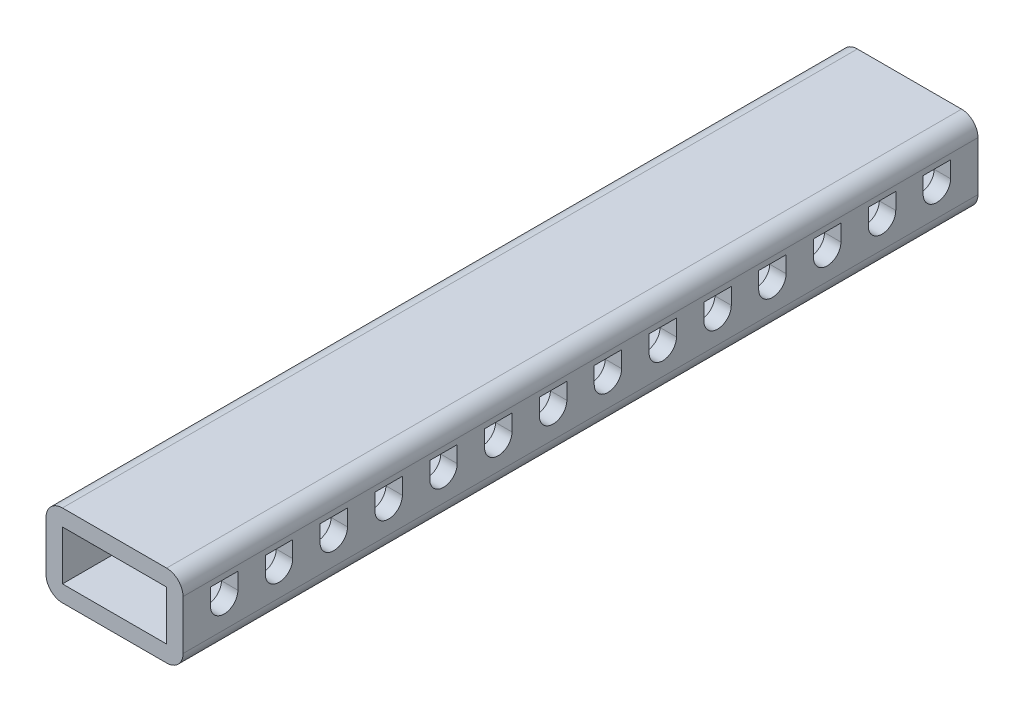
SolidWorks part; units mm, degrees
ref_plane "Front Plane" through (0, 0, 0) normal (0, 0, 1) x (1, 0, 0)
ref_plane "Top Plane" through (0, 0, 0) normal (0, 1, 0) x (1, 0, 0)
ref_plane "Right Plane" through (0, 0, 0) normal (1, 0, 0) x (0, 0, -1)
sketch "Sketch1" plane through (0, 0, 0) normal (0, 0, 1) x (1, 0, 0)
  line L1 (-12.5, 7.5) -> (12.5, 7.5)
  line L2 (-12.5, 7.5) -> (-12.5, -7.5)
  line L3 (-12.5, -7.5) -> (12.5, -7.5)
  line L4 (12.5, 7.5) -> (12.5, -7.5)
  line L5 (-12.5, 7.5) -> (12.5, -7.5) construction
  line L6 (-12.5, -7.5) -> (12.5, 7.5) construction
  point P0 (0, 0)
  dimension "D1" = 25
  dimension "D2" = 15
extrude "Boss-Extrude1" add sketch "Sketch1" along normal blind 145
sketch "Sketch2" plane through (0, 0, 145) normal (0, 0, 1) x (1, 0, 0)
  line L0 (-12.5, 7.5) -> (-12.5, -7.5) construction
  line L1 (-9.5, -4.5) -> (9.5, -4.5)
  line L2 (-9.5, -4.5) -> (-9.5, 4.5)
  line L3 (-9.5, 4.5) -> (9.5, 4.5)
  line L4 (9.5, -4.5) -> (9.5, 4.5)
  line L5 (-9.5, -4.5) -> (9.5, 4.5) construction
  line L6 (-9.5, 4.5) -> (9.5, -4.5) construction
  line L7 (12.5, 7.5) -> (-12.5, 7.5) construction
  point P0 (0, 0)
  dimension "D1" = 3
  dimension "D2" = 3
extrude "Cut-Extrude1" cut sketch "Sketch2" against normal blind 263
sketch "Sketch3" plane through (12.5, 0, 0) normal (1, 0, 0) x (0, 0, -1)
  line L1 (-145, 7.5) -> (0, 7.5) construction
  line L2 (-140, 3.5) -> (-135, 3.5)
  line L3 (-140, 3.5) -> (-140, 0.5)
  line L5 (-135, 3.5) -> (-135, 0.5)
  line L6 (-145, -7.5) -> (-145, 7.5) construction
  line L7 (-132.5, 7.5) -> (-132.5, 3.8883) construction
  line L8 (-130, 3.5) -> (-130, 0.5)
  line L9 (-125, 3.5) -> (-125, 0.5)
  line L10 (-125, 3.5) -> (-130, 3.5)
  line L11 (-122.5, 7.5) -> (-122.5, 3.8883) construction
  line L12 (-112.5, 7.5) -> (-112.5, 3.8883) construction
  line L13 (-120, 3.5) -> (-115, 3.5)
  line L14 (-120, 3.5) -> (-120, 0.5)
  line L15 (-115, 3.5) -> (-115, 0.5)
  line L16 (-110, 3.5) -> (-110, 0.5)
  line L17 (-105, 3.5) -> (-105, 0.5)
  line L18 (-105, 3.5) -> (-110, 3.5)
  line L19 (-102.5, 7.5) -> (-102.5, 3.8883) construction
  line L20 (-92.5, 7.5) -> (-92.5, 3.8883) construction
  line L21 (-110, 3.5) -> (-110, 0.5)
  line L22 (-105, 3.5) -> (-105, 0.5)
  line L23 (-105, 3.5) -> (-110, 3.5)
  line L24 (-100, 3.5) -> (-95, 3.5)
  line L25 (-100, 3.5) -> (-100, 0.5)
  line L26 (-95, 3.5) -> (-95, 0.5)
  line L27 (-90, 3.5) -> (-90, 0.5)
  line L28 (-85, 3.5) -> (-85, 0.5)
  line L29 (-85, 3.5) -> (-90, 3.5)
  line L30 (-82.5, 7.5) -> (-82.5, 3.8883) construction
  line L31 (-72.5, 7.5) -> (-72.5, 3.8883) construction
  line L32 (-62.5, 7.5) -> (-62.5, 3.8883) construction
  line L33 (-52.5, 7.5) -> (-52.5, 3.8883) construction
  line L34 (-90, 3.5) -> (-90, 0.5)
  line L35 (-85, 3.5) -> (-85, 0.5)
  line L36 (-85, 3.5) -> (-90, 3.5)
  line L37 (-80, 3.5) -> (-75, 3.5)
  line L38 (-80, 3.5) -> (-80, 0.5)
  line L39 (-75, 3.5) -> (-75, 0.5)
  line L40 (-80, 3.5) -> (-75, 3.5)
  line L41 (-80, 3.5) -> (-80, 0.5)
  line L42 (-75, 3.5) -> (-75, 0.5)
  line L43 (-70, 3.5) -> (-70, 0.5)
  line L44 (-65, 3.5) -> (-65, 0.5)
  line L45 (-65, 3.5) -> (-70, 3.5)
  line L46 (-60, 3.5) -> (-55, 3.5)
  line L47 (-60, 3.5) -> (-60, 0.5)
  line L48 (-55, 3.5) -> (-55, 0.5)
  line L49 (-50, 3.5) -> (-50, 0.5)
  line L50 (-45, 3.5) -> (-45, 0.5)
  line L51 (-45, 3.5) -> (-50, 3.5)
  line L52 (-42.5, 7.5) -> (-42.5, 3.8883) construction
  line L53 (-32.5, 7.5) -> (-32.5, 3.8883) construction
  line L54 (-22.5, 7.5) -> (-22.5, 3.8883) construction
  line L55 (-12.5, 7.5) -> (-12.5, 3.8883) construction
  line L56 (-2.5, 7.5) -> (-2.5, 3.8883) construction
  line L57 (7.5, 7.5) -> (7.5, 3.8883) construction
  line L58 (17.5, 7.5) -> (17.5, 3.8883) construction
  line L59 (27.5, 7.5) -> (27.5, 3.8883) construction
  line L60 (-50, 3.5) -> (-50, 0.5)
  line L61 (-45, 3.5) -> (-45, 0.5)
  line L62 (-45, 3.5) -> (-50, 3.5)
  line L63 (-40, 3.5) -> (-35, 3.5)
  line L64 (-40, 3.5) -> (-40, 0.5)
  line L65 (-35, 3.5) -> (-35, 0.5)
  line L66 (-30, 3.5) -> (-30, 0.5)
  line L67 (-25, 3.5) -> (-25, 0.5)
  line L68 (-25, 3.5) -> (-30, 3.5)
  line L69 (-30, 3.5) -> (-30, 0.5)
  line L70 (-25, 3.5) -> (-25, 0.5)
  line L71 (-25, 3.5) -> (-30, 3.5)
  line L72 (-20, 3.5) -> (-15, 3.5)
  line L73 (-20, 3.5) -> (-20, 0.5)
  line L74 (-15, 3.5) -> (-15, 0.5)
  line L75 (-20, 3.5) -> (-15, 3.5)
  line L76 (-20, 3.5) -> (-20, 0.5)
  line L77 (-15, 3.5) -> (-15, 0.5)
  line L78 (-10, 3.5) -> (-10, 0.5)
  line L79 (-5, 3.5) -> (-5, 0.5)
  line L80 (-5, 3.5) -> (-10, 3.5)
  line L81 (0, 3.5) -> (5, 3.5)
  line L82 (0, 3.5) -> (0, 0.5)
  line L83 (5, 3.5) -> (5, 0.5)
  line L84 (0, 3.5) -> (5, 3.5)
  line L85 (0, 3.5) -> (0, 0.5)
  line L86 (5, 3.5) -> (5, 0.5)
  line L87 (10, 3.5) -> (10, 0.5)
  line L88 (15, 3.5) -> (15, 0.5)
  line L89 (15, 3.5) -> (10, 3.5)
  line L90 (20, 3.5) -> (25, 3.5)
  line L91 (20, 3.5) -> (20, 0.5)
  line L92 (25, 3.5) -> (25, 0.5)
  line L93 (30, 3.5) -> (30, 0.5)
  line L94 (35, 3.5) -> (35, 0.5)
  line L95 (35, 3.5) -> (30, 3.5)
  line L96 (30, 3.5) -> (30, 0.5)
  line L97 (60, 3.5) -> (65, 3.5)
  line L98 (60, 3.5) -> (60, 0.5)
  line L99 (65, 3.5) -> (65, 0.5)
  line L100 (37.5, 7.5) -> (37.5, 3.8883) construction
  line L101 (47.5, 7.5) -> (47.5, 3.8883) construction
  line L102 (57.5, 7.5) -> (57.5, 3.8883) construction
  line L103 (35, 3.5) -> (35, 0.5)
  line L104 (35, 3.5) -> (30, 3.5)
  line L105 (40, 3.5) -> (45, 3.5)
  line L106 (40, 3.5) -> (40, 0.5)
  line L107 (45, 3.5) -> (45, 0.5)
  line L108 (50, 3.5) -> (50, 0.5)
  line L109 (55, 3.5) -> (55, 0.5)
  line L110 (55, 3.5) -> (50, 3.5)
  line L111 (50, 3.5) -> (50, 0.5)
  line L112 (55, 3.5) -> (55, 0.5)
  line L113 (55, 3.5) -> (50, 3.5)
  line L114 (67.5, 7.5) -> (67.5, 3.8883) construction
  line L115 (60, 3.5) -> (65, 3.5)
  line L116 (60, 3.5) -> (60, 0.5)
  line L117 (65, 3.5) -> (65, 0.5)
  line L118 (60, 3.5) -> (65, 3.5)
  line L119 (60, 3.5) -> (60, 0.5)
  line L120 (65, 3.5) -> (65, 0.5)
  line L121 (70, 3.5) -> (70, 0.5)
  line L122 (75, 3.5) -> (75, 0.5)
  line L123 (75, 3.5) -> (70, 3.5)
  arc A0 (-140, 0.5) -> (-135, 0.5) centre (-137.5, 0.5) ccw
  arc A1 (-125, 0.5) -> (-130, 0.5) centre (-127.5, 0.5) cw
  arc A2 (-120, 0.5) -> (-115, 0.5) centre (-117.5, 0.5) ccw
  arc A3 (-105, 0.5) -> (-110, 0.5) centre (-107.5, 0.5) cw
  arc A4 (-105, 0.5) -> (-110, 0.5) centre (-107.5, 0.5) cw
  arc A5 (-100, 0.5) -> (-95, 0.5) centre (-97.5, 0.5) ccw
  arc A6 (-85, 0.5) -> (-90, 0.5) centre (-87.5, 0.5) cw
  arc A7 (-85, 0.5) -> (-90, 0.5) centre (-87.5, 0.5) cw
  arc A8 (-80, 0.5) -> (-75, 0.5) centre (-77.5, 0.5) ccw
  arc A9 (-80, 0.5) -> (-75, 0.5) centre (-77.5, 0.5) ccw
  arc A10 (-65, 0.5) -> (-70, 0.5) centre (-67.5, 0.5) cw
  arc A11 (-60, 0.5) -> (-55, 0.5) centre (-57.5, 0.5) ccw
  arc A12 (-45, 0.5) -> (-50, 0.5) centre (-47.5, 0.5) cw
  arc A13 (-45, 0.5) -> (-50, 0.5) centre (-47.5, 0.5) cw
  arc A14 (-40, 0.5) -> (-35, 0.5) centre (-37.5, 0.5) ccw
  arc A15 (-25, 0.5) -> (-30, 0.5) centre (-27.5, 0.5) cw
  arc A16 (-25, 0.5) -> (-30, 0.5) centre (-27.5, 0.5) cw
  arc A17 (-20, 0.5) -> (-15, 0.5) centre (-17.5, 0.5) ccw
  arc A18 (-20, 0.5) -> (-15, 0.5) centre (-17.5, 0.5) ccw
  arc A19 (-5, 0.5) -> (-10, 0.5) centre (-7.5, 0.5) cw
  arc A20 (0, 0.5) -> (5, 0.5) centre (2.5, 0.5) ccw
  arc A21 (0, 0.5) -> (5, 0.5) centre (2.5, 0.5) ccw
  arc A22 (15, 0.5) -> (10, 0.5) centre (12.5, 0.5) cw
  arc A23 (20, 0.5) -> (25, 0.5) centre (22.5, 0.5) ccw
  arc A24 (35, 0.5) -> (30, 0.5) centre (32.5, 0.5) cw
  arc A25 (60, 0.5) -> (65, 0.5) centre (62.5, 0.5) ccw
  arc A26 (35, 0.5) -> (30, 0.5) centre (32.5, 0.5) cw
  arc A27 (40, 0.5) -> (45, 0.5) centre (42.5, 0.5) ccw
  arc A28 (55, 0.5) -> (50, 0.5) centre (52.5, 0.5) cw
  arc A29 (55, 0.5) -> (50, 0.5) centre (52.5, 0.5) cw
  arc A30 (60, 0.5) -> (65, 0.5) centre (62.5, 0.5) ccw
  arc A31 (60, 0.5) -> (65, 0.5) centre (62.5, 0.5) ccw
  arc A32 (75, 0.5) -> (70, 0.5) centre (72.5, 0.5) cw
  point P18 (-125, 2)
  dimension "D1" = 4
  dimension "D2" = 5
  dimension "D3" = 5
  dimension "D4" = 3
  dimension "D5" = 5
  dimension "D6" = 5
extrude "Cut-Extrude2" cut sketch "Sketch3" against normal blind 263 contours L3 A0 L5 L2 | A1 L9 L10 L8 | L14 A2 L15 L13 | A3 L17 L18 L16 | L25 A5 L26 L24 | A6 L28 L29 L27 | L38 A8 L39 L37 | A10 L44 L45 L43 | L47 A11 L48 L46 | A12 L50 L51 L49 | L64 A14 L65 L63 | A15 L67 L68 L66 | L73 A17 L74 L72 | A19 L79 L80 L78 | L82 A20 L83 L81 | A22 L88 L89 L87 | L91 A23 L92 L90 | A24 L94 L95 L93 | L106 A27 L107 L105 | A28 L109 L110 L108 | L98 A25 L99 L97 | A32 L122 L123 L121
fillet "Fillet1" radius 3 4 edges at (-12.5, -7.5, 72.5) (12.5, -7.5, 72.5) (12.5, 7.5, 72.5) (-12.5, 7.5, 72.5)
